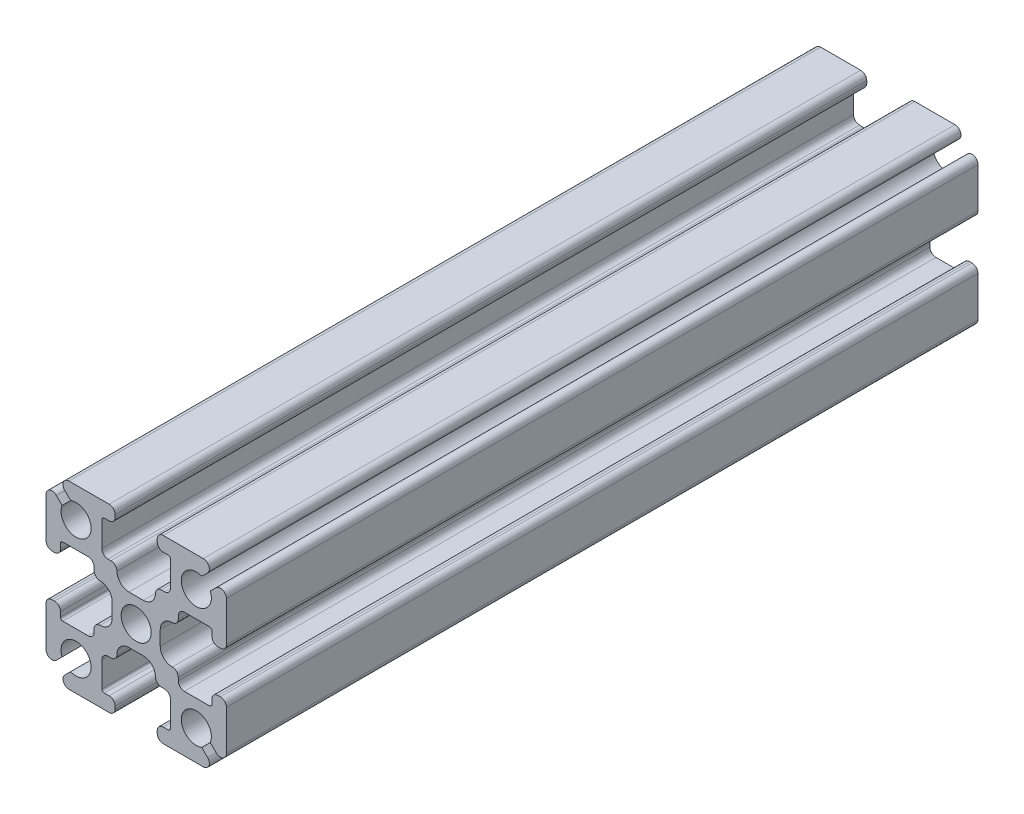
SolidWorks part; units mm, degrees
ref_plane "Front" through (0, 0, 0) normal (0, 0, 1) x (1, 0, 0)
ref_plane "Top" through (0, 0, 0) normal (0, 1, 0) x (1, 0, 0)
ref_plane "Right" through (0, 0, 0) normal (1, 0, 0) x (0, 0, -1)
sketch "Sketch1" plane through (0, 0, 0) normal (0, 0, 1) x (1, 0, 0)
  line L0 (6.6464, 5.9393) -> (6.1636, 5.4565)
  line L1 (5.4565, 6.1636) -> (5.9393, 6.6464)
  line L2 (5.5858, 7.5) -> (2.25, 7.5)
  line L3 (1.75, 7) -> (1.75, 6.8)
  line L4 (2.25, 6.3) -> (2.65, 6.3)
  line L5 (2.85, 6.1) -> (2.85, 4)
  line L6 (2.35, 3.5) -> (2.1, 3.5)
  line L7 (0.6, 2) -> (-0.6, 2)
  line L8 (-2.1, 3.5) -> (-2.35, 3.5)
  line L9 (-2.85, 4) -> (-2.85, 6.1)
  line L10 (-2.65, 6.3) -> (-2.25, 6.3)
  line L11 (-1.75, 6.8) -> (-1.75, 7)
  line L12 (-2.25, 7.5) -> (-5.5858, 7.5)
  line L13 (-5.9393, 6.6464) -> (-5.4565, 6.1636)
  line L14 (-6.1636, 5.4565) -> (-6.6464, 5.9393)
  line L15 (-7.5, 5.5858) -> (-7.5, 2.25)
  line L16 (-7, 1.75) -> (-6.8, 1.75)
  line L17 (-6.3, 2.25) -> (-6.3, 2.65)
  line L18 (-6.1, 2.85) -> (-4, 2.85)
  line L19 (-3.5, 2.35) -> (-3.5, 2.1)
  line L20 (-2, 0.6) -> (-2, -0.6)
  line L21 (-3.5, -2.1) -> (-3.5, -2.35)
  line L22 (-4, -2.85) -> (-6.1, -2.85)
  line L23 (-6.3, -2.65) -> (-6.3, -2.25)
  line L24 (-6.8, -1.75) -> (-7, -1.75)
  line L25 (-7.5, -2.25) -> (-7.5, -5.5858)
  line L26 (-6.6464, -5.9393) -> (-6.1636, -5.4565)
  line L27 (-5.4565, -6.1636) -> (-5.9393, -6.6464)
  line L28 (-5.5858, -7.5) -> (-2.25, -7.5)
  line L29 (-1.75, -7) -> (-1.75, -6.8)
  line L30 (-2.25, -6.3) -> (-2.65, -6.3)
  line L31 (-2.85, -6.1) -> (-2.85, -4)
  line L32 (-2.35, -3.5) -> (-2.1, -3.5)
  line L33 (-0.6, -2) -> (0.6, -2)
  line L34 (2.1, -3.5) -> (2.35, -3.5)
  line L35 (2.85, -4) -> (2.85, -6.1)
  line L36 (2.65, -6.3) -> (2.25, -6.3)
  line L37 (1.75, -6.8) -> (1.75, -7)
  line L38 (2.25, -7.5) -> (5.5858, -7.5)
  line L39 (5.9393, -6.6464) -> (5.4565, -6.1636)
  line L40 (6.1636, -5.4565) -> (6.6464, -5.9393)
  line L41 (7.5, -5.5858) -> (7.5, -2.25)
  line L42 (7, -1.75) -> (6.8, -1.75)
  line L43 (6.3, -2.25) -> (6.3, -2.65)
  line L44 (6.1, -2.85) -> (4, -2.85)
  line L45 (3.5, -2.35) -> (3.5, -2.1)
  line L46 (2, -0.6) -> (2, 0.6)
  line L47 (3.5, 2.1) -> (3.5, 2.35)
  line L48 (4, 2.85) -> (6.1, 2.85)
  line L49 (6.3, 2.65) -> (6.3, 2.25)
  line L50 (6.8, 1.75) -> (7, 1.75)
  line L51 (7.5, 2.25) -> (7.5, 5.5858)
  circle A0 centre (0, 0) radius 1.25
  arc A1 (6.1636, 5.4565) -> (5.4565, 6.1636) centre (5, 5) cw
  arc A2 (5.9393, 6.6464) -> (5.5858, 7.5) centre (5.5858, 7) ccw
  arc A3 (2.25, 7.5) -> (1.75, 7) centre (2.25, 7) ccw
  arc A4 (1.75, 6.8) -> (2.25, 6.3) centre (2.25, 6.8) ccw
  arc A5 (2.65, 6.3) -> (2.85, 6.1) centre (2.65, 6.1) cw
  arc A6 (2.85, 4) -> (2.35, 3.5) centre (2.35, 4) cw
  arc A7 (2.1, 3.5) -> (1.6, 3) centre (2.1, 3) ccw
  arc A8 (1.6, 3) -> (0.6, 2) centre (0.6, 3) cw
  arc A9 (-0.6, 2) -> (-1.6, 3) centre (-0.6, 3) cw
  arc A10 (-1.6, 3) -> (-2.1, 3.5) centre (-2.1, 3) ccw
  arc A11 (-2.35, 3.5) -> (-2.85, 4) centre (-2.35, 4) cw
  arc A12 (-2.85, 6.1) -> (-2.65, 6.3) centre (-2.65, 6.1) cw
  arc A13 (-2.25, 6.3) -> (-1.75, 6.8) centre (-2.25, 6.8) ccw
  arc A14 (-1.75, 7) -> (-2.25, 7.5) centre (-2.25, 7) ccw
  arc A15 (-5.5858, 7.5) -> (-5.9393, 6.6464) centre (-5.5858, 7) ccw
  arc A16 (-5.4565, 6.1636) -> (-6.1636, 5.4565) centre (-5, 5) cw
  arc A17 (-6.6464, 5.9393) -> (-7.5, 5.5858) centre (-7, 5.5858) ccw
  arc A18 (-7.5, 2.25) -> (-7, 1.75) centre (-7, 2.25) ccw
  arc A19 (-6.8, 1.75) -> (-6.3, 2.25) centre (-6.8, 2.25) ccw
  arc A20 (-6.3, 2.65) -> (-6.1, 2.85) centre (-6.1, 2.65) cw
  arc A21 (-4, 2.85) -> (-3.5, 2.35) centre (-4, 2.35) cw
  arc A22 (-3.5, 2.1) -> (-3, 1.6) centre (-3, 2.1) ccw
  arc A23 (-3, 1.6) -> (-2, 0.6) centre (-3, 0.6) cw
  arc A24 (-2, -0.6) -> (-3, -1.6) centre (-3, -0.6) cw
  arc A25 (-3, -1.6) -> (-3.5, -2.1) centre (-3, -2.1) ccw
  arc A26 (-3.5, -2.35) -> (-4, -2.85) centre (-4, -2.35) cw
  arc A27 (-6.1, -2.85) -> (-6.3, -2.65) centre (-6.1, -2.65) cw
  arc A28 (-6.3, -2.25) -> (-6.8, -1.75) centre (-6.8, -2.25) ccw
  arc A29 (-7, -1.75) -> (-7.5, -2.25) centre (-7, -2.25) ccw
  arc A30 (-7.5, -5.5858) -> (-6.6464, -5.9393) centre (-7, -5.5858) ccw
  arc A31 (-6.1636, -5.4565) -> (-5.4565, -6.1636) centre (-5, -5) cw
  arc A32 (-5.9393, -6.6464) -> (-5.5858, -7.5) centre (-5.5858, -7) ccw
  arc A33 (-2.25, -7.5) -> (-1.75, -7) centre (-2.25, -7) ccw
  arc A34 (-1.75, -6.8) -> (-2.25, -6.3) centre (-2.25, -6.8) ccw
  arc A35 (-2.65, -6.3) -> (-2.85, -6.1) centre (-2.65, -6.1) cw
  arc A36 (-2.85, -4) -> (-2.35, -3.5) centre (-2.35, -4) cw
  arc A37 (-2.1, -3.5) -> (-1.6, -3) centre (-2.1, -3) ccw
  arc A38 (-1.6, -3) -> (-0.6, -2) centre (-0.6, -3) cw
  arc A39 (0.6, -2) -> (1.6, -3) centre (0.6, -3) cw
  arc A40 (1.6, -3) -> (2.1, -3.5) centre (2.1, -3) ccw
  arc A41 (2.35, -3.5) -> (2.85, -4) centre (2.35, -4) cw
  arc A42 (2.85, -6.1) -> (2.65, -6.3) centre (2.65, -6.1) cw
  arc A43 (2.25, -6.3) -> (1.75, -6.8) centre (2.25, -6.8) ccw
  arc A44 (1.75, -7) -> (2.25, -7.5) centre (2.25, -7) ccw
  arc A45 (5.5858, -7.5) -> (5.9393, -6.6464) centre (5.5858, -7) ccw
  arc A46 (5.4565, -6.1636) -> (6.1636, -5.4565) centre (5, -5) cw
  arc A47 (6.6464, -5.9393) -> (7.5, -5.5858) centre (7, -5.5858) ccw
  arc A48 (7.5, -2.25) -> (7, -1.75) centre (7, -2.25) ccw
  arc A49 (6.8, -1.75) -> (6.3, -2.25) centre (6.8, -2.25) ccw
  arc A50 (6.3, -2.65) -> (6.1, -2.85) centre (6.1, -2.65) cw
  arc A51 (4, -2.85) -> (3.5, -2.35) centre (4, -2.35) cw
  arc A52 (3.5, -2.1) -> (3, -1.6) centre (3, -2.1) ccw
  arc A53 (3, -1.6) -> (2, -0.6) centre (3, -0.6) cw
  arc A54 (2, 0.6) -> (3, 1.6) centre (3, 0.6) cw
  arc A55 (3, 1.6) -> (3.5, 2.1) centre (3, 2.1) ccw
  arc A56 (3.5, 2.35) -> (4, 2.85) centre (4, 2.35) cw
  arc A57 (6.1, 2.85) -> (6.3, 2.65) centre (6.1, 2.65) cw
  arc A58 (6.3, 2.25) -> (6.8, 1.75) centre (6.8, 2.25) ccw
  arc A59 (7, 1.75) -> (7.5, 2.25) centre (7, 2.25) ccw
  arc A60 (7.5, 5.5858) -> (6.6464, 5.9393) centre (7, 5.5858) ccw
extrude "Boss-Extrude1" add sketch "Sketch1" along normal blind 62.5
